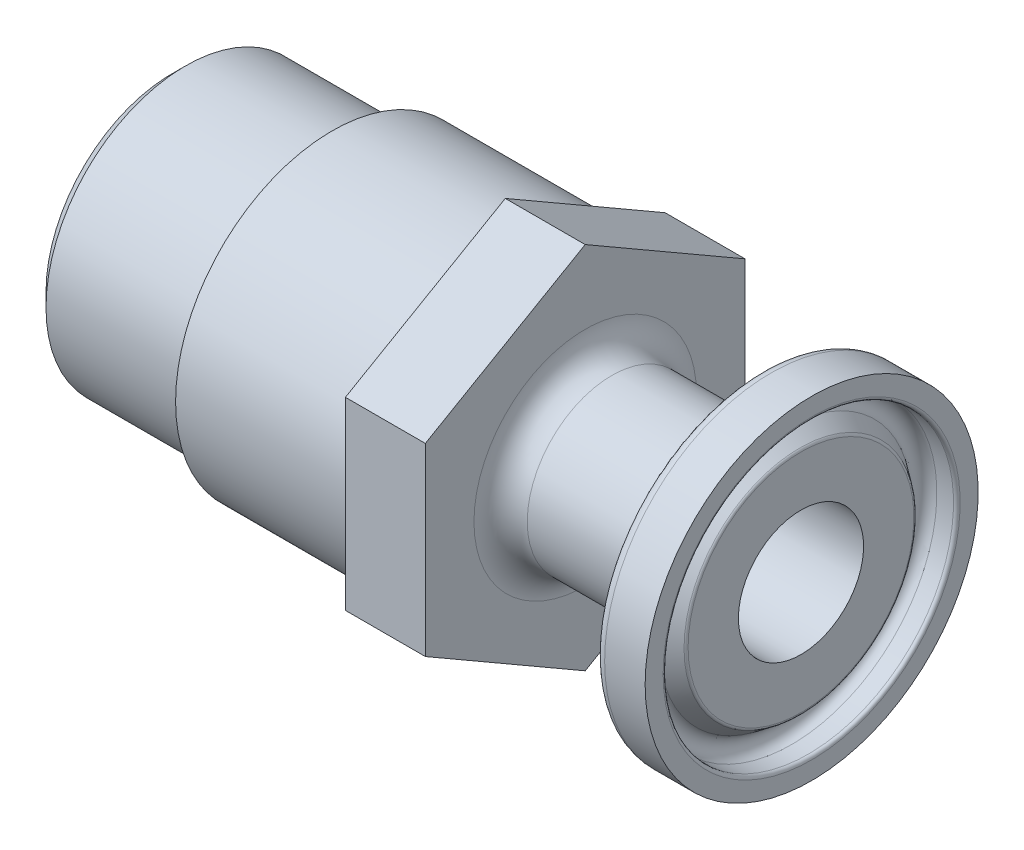
SolidWorks part; units mm, degrees
material "1.4301 (X5CrNi18-10)"
ref_plane "Vorne" through (0, 0, 0) normal (0, 0, 1) x (1, 0, 0)
ref_plane "Oben" through (0, 0, 0) normal (0, 1, 0) x (1, 0, 0)
ref_plane "Rechts" through (0, 0, 0) normal (1, 0, 0) x (0, 0, -1)
sketch "Skizze1" plane through (0, 0, 0) normal (0, 0, 1) x (1, 0, 0)
  line L0 (0, 0) -> (52.9667, 0) construction
  line L1 (47.75, 10.9) -> (46.5, 10.9)
  line L2 (0, 4.7) -> (47.2, 4.7)
  line L3 (31, 8.35) -> (31, 15)
  line L4 (48, 12.5) -> (44.9602, 12.5)
  line L5 (44.2084, 11.9736) -> (42.6406, 7.666)
  line L6 (40.7612, 6.35) -> (33, 6.35)
  line L7 (48, 11.15) -> (48, 12.5)
  line L8 (46.0298, 9.4528) -> (47.0969, 8.6774)
  line L9 (47.2, 8.4752) -> (47.2, 4.7)
  line L10 (42.6406, 7.666) -> (44.8971, 13.8657) construction
  line L11 (48, 12.5) -> (44.4, 12.5) construction
  line L12 (31, 15) -> (25, 15)
  line L13 (12, 11.75) -> (12, 10.9775)
  line L14 (11.5, 10.4775) -> (1, 10.4775)
  line L15 (1, 10.4775) -> (0, 9.4775)
  line L16 (12, 11.75) -> (25, 11.75)
  line L17 (25, 11.75) -> (25, 15)
  line L19 (0, 9.4775) -> (0, 4.7)
  arc A0 (48, 11.15) -> (47.75, 10.9) centre (47.75, 11.15) cw
  arc A1 (42.6406, 7.666) -> (40.7612, 6.35) centre (40.7612, 8.35) cw
  arc A2 (47.0969, 8.6774) -> (47.2, 8.4752) centre (46.95, 8.4752) cw
  arc A3 (46.5, 10.9) -> (46.0298, 9.4528) centre (46.5, 10.1) ccw
  arc A4 (33, 6.35) -> (31, 8.35) centre (33, 8.35) cw
  arc A5 (44.9602, 12.5) -> (44.2084, 11.9736) centre (44.9602, 11.7) ccw
  arc A6 (12, 10.9775) -> (11.5, 10.4775) centre (11.5, 10.9775) cw
  point P18 (44.4, 12.5)
  point P22 (0, 10.4775)
  point P32 (44.4, 12.5)
  dimension "D8" = 0.25
  dimension "D16" = 2
  dimension "D20" = 12
  dimension "D21" = 13
  dimension "D23" = 6
  dimension "D6" = 0.25
  dimension "D10" = 1.6
  dimension "D14" = 0.8
  dimension "D9" = 2.3
  dimension "D17" = 2
  dimension "D19" = 0.5
  dimension "D1" = 9.4
  dimension "D2" = 12.7
  dimension "D3" = 3.6
  dimension "D4" = 48
  dimension "D5" = 36
  dimension "D7" = 0.8
  dimension "D11" = 20.2
  dimension "D12" = 25
  dimension "D13" = 20
  dimension "D15" = 30
  dimension "D18" = 20.955
  dimension "D24" = 23.5
revolve "Rotation1" add sketch "Skizze1" angle 360 about L0
sketch "Skizze2" plane through (0, 0, 0) normal (-1, 0, 0) x (0, 0, 1)
  line L0 (0, 0) -> (19.3849, 0) construction
  line L2 (-12, -6.9282) -> (0, -13.8564)
  line L3 (0, -13.8564) -> (12, -6.9282)
  line L4 (12, -6.9282) -> (12, 6.9282)
  line L5 (12, 6.9282) -> (0, 13.8564)
  line L6 (0, 13.8564) -> (-12, 6.9282)
  line L7 (-12, 6.9282) -> (-12, -6.9282)
  circle A0 centre (0, 0) radius 12 construction
  circle A1 centre (0, 0) radius 15
  circle A4 centre (0, 0) radius 15 construction
  dimension "D1" = 24
extrude "Schnitt-Linear austragen1" cut sketch "Skizze2" against normal blind 38
